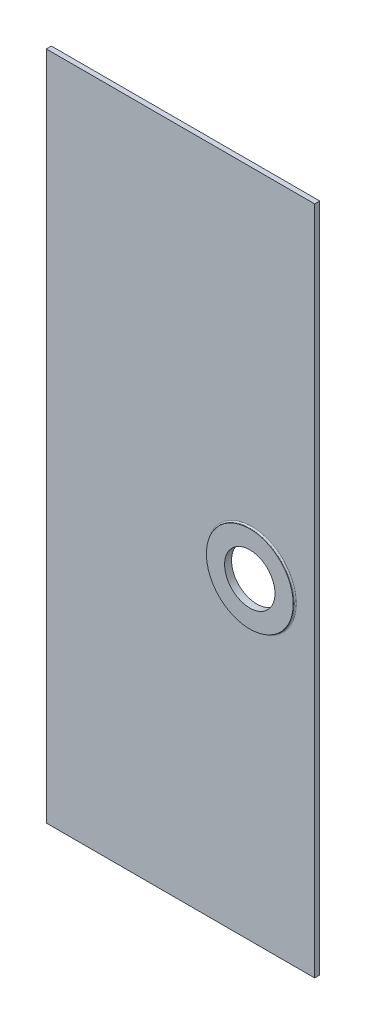
SolidWorks part; units mm, degrees
ref_plane "Front Plane" through (0, 0, 0) normal (0, 0, 1) x (1, 0, 0)
ref_plane "Top Plane" through (0, 0, 0) normal (0, 1, 0) x (1, 0, 0)
ref_plane "Right Plane" through (0, 0, 0) normal (1, 0, 0) x (0, 0, -1)
sketch "Sketch1" plane through (0, 0, 0) normal (0, 0, 1) x (1, 0, 0)
  line L1 (0, 0) -> (106.5, 0)
  line L2 (0, 0) -> (0, -266)
  line L3 (0, -266) -> (106.5, -266)
  line L4 (106.5, 0) -> (106.5, -266)
  dimension "D1" = 266
  dimension "D2" = 106.5
extrude "Boss-Extrude1" add sketch "Sketch1" along normal blind 2
sketch "Sketch2" plane through (0, 0, 2) normal (0, 0, 1) x (1, 0, 0)
  line L0 (0, -266) -> (106.5, -266) construction
  line L1 (106.5, -266) -> (106.5, 0) construction
  circle A0 centre (81.5, -141) radius 10
  dimension "D3" = 20
  dimension "D1" = 125
  dimension "D2" = 25
extrude "Cut-Extrude1" cut sketch "Sketch2" against normal blind 10
sketch "Sketch5" plane through (0, 0, 2) normal (0, 0, 1) x (1, 0, 0)
  circle A0 centre (81.5, -141) radius 17.2214
  circle A1 centre (81.5, -141) radius 10 construction
extrude "Boss-Extrude3" add sketch "Sketch5" along normal blind 0.75
fillet "Fillet2" radius 0.5 1 edges at (98.7214, -141, 2)
sketch "Sketch6" plane through (0, 0, 2) normal (0, 0, -1) x (-1, 0, 0)
  circle A1 centre (-81.5, -141) radius 10
  circle A2 centre (-81.5, -141) radius 10
  dimension "D1" = 0
extrude "Cut-Extrude3" cut sketch "Sketch6" against normal blind 0.75
